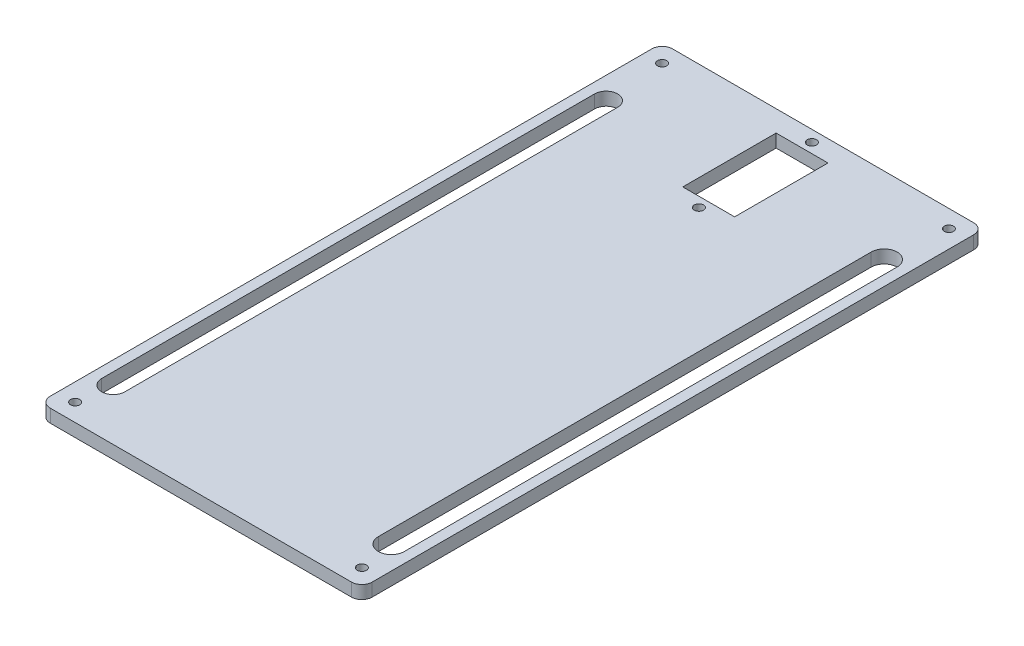
SolidWorks part; units mm, degrees
material "Brass"
ref_plane "Front Plane" through (0, 0, 0) normal (0, 0, 1) x (1, 0, 0)
ref_plane "Top Plane" through (0, 0, 0) normal (0, 1, 0) x (1, 0, 0)
ref_plane "Right Plane" through (0, 0, 0) normal (1, 0, 0) x (0, 0, -1)
sketch "Sketch2" plane through (0, 0, 0) normal (0, 0, 1) x (1, 0, 0)
  line L0 (-44.45, 0) -> (-44.45, -3.2004)
  line L1 (0, 0) -> (0, -3.2004) construction
  line L2 (-44.45, -3.2004) -> (34.3945, -3.2004)
  line L3 (34.3945, 0) -> (34.3945, -3.2004)
  line L4 (-44.45, 0) -> (34.3945, 0)
  dimension "D1" = 78.8445
  dimension "D2" = 3.2004
extrude "Boss-Extrude1" add sketch "Sketch2" along normal blind 152.4 contours L4 L3 L2 L0
sketch "Sketch3" plane through (0, -3.2004, 0) normal (0, -1, 0) x (1, 0, 0)
  line L1 (30.0765, 152.4) -> (30.0765, 148.082) construction
  line L2 (30.0765, 148.082) -> (34.3945, 148.082) construction
  line L3 (-44.45, 152.4) -> (34.3945, 152.4) construction
  line L4 (-5.0278, 30.4259) -> (-5.0278, 0) construction
  line L5 (-44.45, 0) -> (34.3945, 0) construction
  line L6 (-41.91, 19.0974) -> (-36.2424, 19.0974) construction
  line L7 (-41.91, 19.0974) -> (-41.91, 139.804)
  line L8 (-41.91, 139.804) -> (-36.2424, 139.804) construction
  line L9 (-36.2424, 19.0974) -> (-36.2424, 139.804)
  line L10 (-39.0762, 152.4) -> (-39.0762, 142.6379) construction
  line L11 (-41.91, 79.4507) -> (-44.45, 79.4507) construction
  line L12 (25.5045, 18.7562) -> (31.8545, 18.7562) construction
  line L13 (25.5045, 18.7562) -> (25.5045, 139.4629)
  line L14 (25.5045, 139.4629) -> (31.8545, 139.4629) construction
  line L15 (31.8545, 18.7562) -> (31.8545, 139.4629)
  line L16 (28.6795, 152.4) -> (28.6795, 142.6379) construction
  line L17 (34.3945, 79.1096) -> (31.8545, 79.1096) construction
  line L18 (34.3945, 152.4) -> (34.3945, 0) construction
  line L19 (-44.45, 4.318) -> (-40.132, 4.318) construction
  line L20 (34.3945, 152.4) -> (34.3945, 0) construction
  line L21 (-44.45, 152.4) -> (-44.45, 0) construction
  line L22 (-44.45, 152.4) -> (-44.45, 0) construction
  line L23 (-40.132, 152.4) -> (-40.132, 148.082) construction
  line L24 (-44.45, 148.082) -> (-40.132, 148.082) construction
  line L25 (-44.45, 152.4) -> (34.3945, 152.4) construction
  line L26 (-40.132, 4.318) -> (-40.132, 0) construction
  line L27 (-44.45, 0) -> (34.3945, 0) construction
  line L28 (34.3945, 4.318) -> (30.0765, 4.318) construction
  line L29 (30.0765, 0) -> (30.0765, 4.318) construction
  line L30 (-11.3778, 28.0256) -> (-11.3778, 5.1656)
  line L31 (1.3222, 28.0256) -> (1.3222, 5.1656)
  line L32 (-11.3778, 5.1656) -> (1.3222, 5.1656)
  line L33 (-11.3778, 28.0256) -> (1.3222, 28.0256)
  arc A1 (-41.91, 139.804) -> (-36.2424, 139.804) centre (-39.0762, 139.804) cw
  arc A2 (-36.2424, 19.0974) -> (-41.91, 19.0974) centre (-39.0762, 19.0974) cw
  arc A3 (25.5045, 139.4629) -> (31.8545, 139.4629) centre (28.6795, 139.4629) cw
  arc A4 (31.8545, 18.7562) -> (25.5045, 18.7562) centre (28.6795, 18.7562) cw
  circle A5 centre (-40.132, 148.082) radius 1.1303
  circle A6 centre (30.0765, 148.082) radius 1.1303
  circle A7 centre (-40.132, 4.318) radius 1.1303
  circle A8 centre (30.0765, 4.318) radius 1.1303
  circle A9 centre (-5.0278, 30.4259) radius 1.1303
  circle A10 centre (-5.0278, 2.7653) radius 1.1303
  point P53 (-5.0278, 28.0256)
  point P58 (-5.0278, 28.0256)
  point P67 (-5.0278, 5.1656)
  dimension "D11" = 2.2606
  dimension "D15" = 2.2606
  dimension "D16" = 2.7653
  dimension "D18" = 2.4003
  dimension "D4" = 5.6676
  dimension "D5" = 9.7621
  dimension "D6" = 2.54
  dimension "D7" = 120.7066
  dimension "D8" = 6.35
  dimension "D9" = 9.7621
  dimension "D10" = 2.54
  dimension "D12" = 4.318
  dimension "D13" = 22.86
  dimension "D14" = 12.7
  dimension "D17" = 2.4003
extrude "Cut-Extrude1" cut sketch "Sketch3" against normal through all
fillet "Fillet1" radius 2.54 4 edges at (34.3945, -1.6002, 152.4) (-44.45, -1.6002, 152.4) (-44.45, -1.6002, 0) (34.3945, -1.6002, 0)
sketch "Sketch4" plane through (0, 0, 210.82) normal (0, 0, 1) x (1, 0, 0)
  line L0 (-5.0278, 0) -> (-5.0278, -3.2004) construction
  line L1 (-44.45, 0) -> (34.3945, 0) construction
  line L2 (-44.45, -3.2004) -> (34.3945, -3.2004) construction
sketch "Sketch6" plane through (34.3945, 0, 0) normal (1, 0, 0) x (0, 0, -1)
  line L0 (-105.41, 0) -> (-105.41, -3.2004) construction
  line L3 (-210.82, -3.2004) -> (0, -3.2004) construction
  line L4 (-210.82, 0) -> (0, 0) construction
